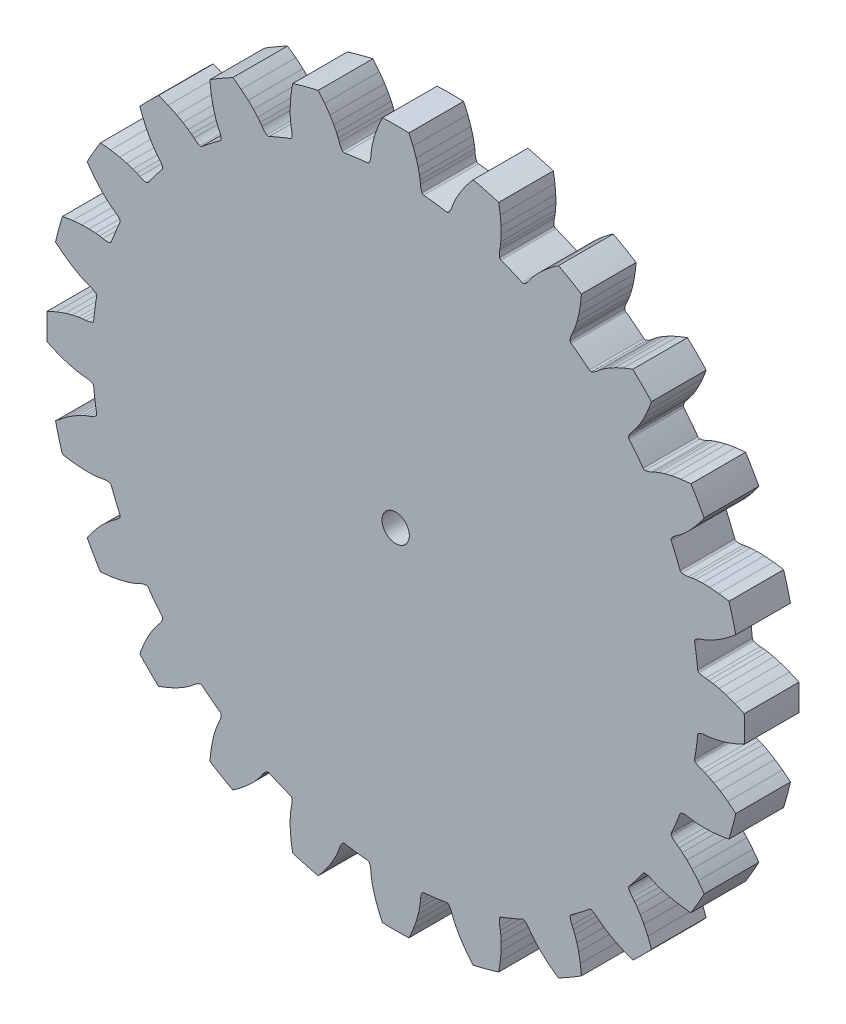
SolidWorks part; units mm, degrees
ref_plane "Front Plane" through (0, 0, 0) normal (0, 0, 1) x (1, 0, 0)
ref_plane "Top Plane" through (0, 0, 0) normal (0, 1, 0) x (1, 0, 0)
ref_plane "Right Plane" through (0, 0, 0) normal (1, 0, 0) x (0, 0, -1)
sketch "Model" plane through (0, 0, 0) normal (0, 0, 1) x (1, 0, 0)
  arc A1 (34.9181, -4.5971) -> (35.0673, -3.2696) centre (0, 0) ccw
  arc A2 (35.2278, -3.0481) -> (35.0673, -3.2696) centre (35.3347, -3.2945) ccw
  arc A3 (35.9833, -2.8721) -> (35.2278, -3.0481) centre (36.0877, -5.0299) ccw
  arc A4 (35.9833, -2.8721) -> (36.3636, -2.8405) centre (35.7172, 2.6237) ccw
  arc A5 (36.3636, -2.8405) -> (36.8336, -2.7716) centre (35.3622, 5.6245) ccw
  arc A6 (36.8336, -2.7716) -> (37.5555, -2.6174) centre (35.1043, 7.0963) ccw
  arc A7 (37.5555, -2.6174) -> (38.3737, -2.3829) centre (34.2966, 10.2971) ccw
  arc A8 (38.3737, -2.3829) -> (39.3866, -2.0164) centre (33.8084, 11.8154) ccw
  arc A9 (39.3866, -2.0164) -> (40.4752, -1.5354) centre (32.5769, 14.869) ccw
  arc A10 (40.4752, -1.5354) -> (40.4752, 1.5354) centre (0, 0) ccw
  arc A11 (40.4752, 1.5354) -> (39.3866, 2.0164) centre (32.5769, -14.869) ccw
  arc A12 (39.3866, 2.0164) -> (38.3737, 2.3829) centre (33.8084, -11.8154) ccw
  arc A13 (38.3737, 2.3829) -> (37.5555, 2.6174) centre (34.2966, -10.2971) ccw
  arc A14 (37.5555, 2.6174) -> (36.8336, 2.7716) centre (35.1043, -7.0963) ccw
  arc A15 (36.8336, 2.7716) -> (36.3636, 2.8405) centre (35.3622, -5.6245) ccw
  arc A16 (36.3636, 2.8405) -> (35.9833, 2.8721) centre (35.7172, -2.6237) ccw
  arc A17 (35.2278, 3.0481) -> (35.9833, 2.8721) centre (36.0877, 5.0299) ccw
  arc A18 (35.0673, 3.2696) -> (35.2278, 3.0481) centre (35.3347, 3.2945) ccw
  arc A19 (35.0673, 3.2696) -> (34.7187, 5.9179) centre (0, 0) ccw
  arc A20 (34.8164, 6.1734) -> (34.7187, 5.9179) centre (34.9834, 5.9631) ccw
  arc A21 (35.5005, 6.5389) -> (34.8164, 6.1734) centre (36.1599, 4.4817) ccw
  arc A22 (35.5005, 6.5389) -> (35.8597, 6.6679) centre (33.8211, 11.7785) ccw
  arc A23 (35.8597, 6.6679) -> (36.2958, 6.8561) centre (32.7015, 14.5853) ccw
  arc A24 (36.2958, 6.8561) -> (36.9533, 7.1918) centre (32.0715, 15.9402) ccw
  arc A25 (36.9533, 7.1918) -> (37.6829, 7.6301) centre (30.4629, 18.8229) ccw
  arc A26 (37.6829, 7.6301) -> (38.5664, 8.2463) centre (29.5984, 20.1631) ccw
  arc A27 (38.5664, 8.2463) -> (39.4934, 8.9927) centre (27.6185, 22.7939) ccw
  arc A28 (39.4934, 8.9927) -> (38.6987, 11.9589) centre (0, 0) ccw
  arc A29 (38.6987, 11.9589) -> (37.5227, 12.1417) centre (35.3153, -5.9309) ccw
  arc A30 (37.5227, 12.1417) -> (36.4494, 12.2336) centre (35.7145, -2.6625) ccw
  arc A31 (36.4494, 12.2336) -> (35.5984, 12.2483) centre (35.7931, -1.0696) ccw
  arc A32 (35.5984, 12.2483) -> (34.8612, 12.2104) centre (35.7448, 2.2311) ccw
  arc A33 (34.8612, 12.2104) -> (34.3894, 12.1553) centre (35.613, 3.7195) ccw
  arc A34 (34.3894, 12.1553) -> (34.0138, 12.0874) centre (35.1792, 6.71) ccw
  arc A35 (33.2386, 12.0619) -> (34.0138, 12.0874) centre (33.5562, 14.1987) ccw
  arc A36 (33.0262, 12.2343) -> (33.2386, 12.0619) centre (33.2781, 12.3275) ccw
  arc A37 (33.0262, 12.2343) -> (32.004, 14.7021) centre (0, 0) ccw
  arc A38 (32.0323, 14.9742) -> (32.004, 14.7021) centre (32.248, 14.8142) ccw
  arc A39 (32.5985, 15.5043) -> (32.0323, 14.9742) centre (33.7678, 13.6878) ccw
  arc A40 (32.5985, 15.5043) -> (32.912, 15.7219) centre (29.6202, 20.1308) ccw
  arc A41 (32.912, 15.7219) -> (33.2846, 16.0165) centre (27.8123, 22.5521) ccw
  arc A42 (33.2846, 16.0165) -> (33.8327, 16.511) centre (26.853, 23.6978) ccw
  arc A43 (33.8327, 16.511) -> (34.4241, 17.1232) centre (24.5532, 26.0659) ccw
  arc A44 (34.4241, 17.1232) -> (35.118, 17.9471) centre (23.3712, 27.1366) ccw
  arc A45 (35.118, 17.9471) -> (35.8203, 18.9079) centre (20.7779, 29.1654) ccw
  arc A46 (35.8203, 18.9079) -> (34.2849, 21.5673) centre (0, 0) ccw
  arc A47 (34.2849, 21.5673) -> (33.1016, 21.4395) centre (35.647, 3.4115) ccw
  arc A48 (33.1016, 21.4395) -> (32.0412, 21.2505) centre (35.1866, 6.6718) ccw
  arc A49 (32.0412, 21.2505) -> (31.2153, 21.0445) centre (34.8503, 8.2307) ccw
  arc A50 (31.2153, 21.0445) -> (30.513, 20.817) centre (33.9494, 11.4065) ccw
  arc A51 (30.513, 20.817) -> (30.0715, 20.6417) centre (33.4369, 12.8101) ccw
  arc A52 (30.0715, 20.6417) -> (29.7263, 20.479) centre (32.2438, 15.5865) ccw
  arc A53 (28.9841, 20.2537) -> (29.7263, 20.479) centre (28.7379, 22.3999) ccw
  arc A54 (28.7344, 20.3652) -> (28.9841, 20.2537) centre (28.9535, 20.5205) ccw
  arc A55 (28.7344, 20.3652) -> (27.1083, 22.4844) centre (0, 0) ccw
  arc A56 (27.0652, 22.7545) -> (27.1083, 22.4844) centre (27.315, 22.6559) ccw
  arc A57 (27.4749, 23.4131) -> (27.0652, 22.7545) centre (29.0746, 21.9612) ccw
  arc A58 (27.4749, 23.4131) -> (27.7215, 23.7044) centre (23.4007, 27.1111) ccw
  arc A59 (27.7215, 23.7044) -> (28.0051, 24.0855) centre (21.0277, 28.982) ccw
  arc A60 (28.0051, 24.0855) -> (28.4066, 24.7049) centre (19.8046, 29.8404) ccw
  arc A61 (28.4066, 24.7049) -> (28.8193, 25.4493) centre (16.9702, 31.5325) ccw
  arc A62 (28.8193, 25.4493) -> (29.2763, 26.4247) centre (15.5514, 32.2609) ccw
  arc A63 (29.2763, 26.4247) -> (29.706, 27.5346) centre (12.5214, 33.5494) ccw
  arc A64 (29.706, 27.5346) -> (27.5346, 29.706) centre (0, 0) ccw
  arc A65 (27.5346, 29.706) -> (26.4247, 29.2763) centre (33.5494, 12.5214) ccw
  arc A66 (26.4247, 29.2763) -> (25.4493, 28.8193) centre (32.2609, 15.5514) ccw
  arc A67 (25.4493, 28.8193) -> (24.7049, 28.4066) centre (31.5325, 16.9702) ccw
  arc A68 (24.7049, 28.4066) -> (24.0855, 28.0051) centre (29.8404, 19.8046) ccw
  arc A69 (24.0855, 28.0051) -> (23.7044, 27.7215) centre (28.982, 21.0277) ccw
  arc A70 (23.7044, 27.7215) -> (23.4131, 27.4749) centre (27.1111, 23.4007) ccw
  arc A71 (22.7545, 27.0652) -> (23.4131, 27.4749) centre (21.9612, 29.0746) ccw
  arc A72 (22.4844, 27.1083) -> (22.7545, 27.0652) centre (22.6559, 27.315) ccw
  arc A73 (22.4844, 27.1083) -> (20.3652, 28.7344) centre (0, 0) ccw
  arc A74 (20.2537, 28.9841) -> (20.3652, 28.7344) centre (20.5205, 28.9535) ccw
  arc A75 (20.479, 29.7263) -> (20.2537, 28.9841) centre (22.3999, 28.7379) ccw
  arc A76 (20.479, 29.7263) -> (20.6417, 30.0715) centre (15.5865, 32.2438) ccw
  arc A77 (20.6417, 30.0715) -> (20.817, 30.513) centre (12.8101, 33.4369) ccw
  arc A78 (20.817, 30.513) -> (21.0445, 31.2153) centre (11.4065, 33.9494) ccw
  arc A79 (21.0445, 31.2153) -> (21.2505, 32.0412) centre (8.2307, 34.8503) ccw
  arc A80 (21.2505, 32.0412) -> (21.4395, 33.1016) centre (6.6718, 35.1866) ccw
  arc A81 (21.4395, 33.1016) -> (21.5673, 34.2849) centre (3.4115, 35.647) ccw
  arc A82 (21.5673, 34.2849) -> (18.9079, 35.8203) centre (0, 0) ccw
  arc A83 (18.9079, 35.8203) -> (17.9471, 35.118) centre (29.1654, 20.7779) ccw
  arc A84 (17.9471, 35.118) -> (17.1232, 34.4241) centre (27.1366, 23.3712) ccw
  arc A85 (17.1232, 34.4241) -> (16.511, 33.8327) centre (26.0659, 24.5532) ccw
  arc A86 (16.511, 33.8327) -> (16.0165, 33.2846) centre (23.6978, 26.853) ccw
  arc A87 (16.0165, 33.2846) -> (15.7219, 32.912) centre (22.5521, 27.8123) ccw
  arc A88 (15.7219, 32.912) -> (15.5043, 32.5985) centre (20.1308, 29.6202) ccw
  arc A89 (14.9742, 32.0323) -> (15.5043, 32.5985) centre (13.6878, 33.7678) ccw
  arc A90 (14.7021, 32.004) -> (14.9742, 32.0323) centre (14.8142, 32.248) ccw
  arc A91 (14.7021, 32.004) -> (12.2343, 33.0262) centre (0, 0) ccw
  arc A92 (12.0619, 33.2386) -> (12.2343, 33.0262) centre (12.3275, 33.2781) ccw
  arc A93 (12.0874, 34.0138) -> (12.0619, 33.2386) centre (14.1987, 33.5562) ccw
  arc A94 (12.0874, 34.0138) -> (12.1553, 34.3894) centre (6.71, 35.1792) ccw
  arc A95 (12.1553, 34.3894) -> (12.2104, 34.8612) centre (3.7195, 35.613) ccw
  arc A96 (12.2104, 34.8612) -> (12.2483, 35.5984) centre (2.2311, 35.7448) ccw
  arc A97 (12.2483, 35.5984) -> (12.2336, 36.4494) centre (-1.0696, 35.7931) ccw
  arc A98 (12.2336, 36.4494) -> (12.1417, 37.5227) centre (-2.6625, 35.7145) ccw
  arc A99 (12.1417, 37.5227) -> (11.9589, 38.6987) centre (-5.9309, 35.3153) ccw
  arc A100 (11.9589, 38.6987) -> (8.9927, 39.4934) centre (0, 0) ccw
  arc A101 (8.9927, 39.4934) -> (8.2463, 38.5664) centre (22.7939, 27.6185) ccw
  arc A102 (8.2463, 38.5664) -> (7.6301, 37.6829) centre (20.1631, 29.5984) ccw
  arc A103 (7.6301, 37.6829) -> (7.1918, 36.9533) centre (18.8229, 30.4629) ccw
  arc A104 (7.1918, 36.9533) -> (6.8561, 36.2958) centre (15.9402, 32.0715) ccw
  arc A105 (6.8561, 36.2958) -> (6.6679, 35.8597) centre (14.5853, 32.7015) ccw
  arc A106 (6.6679, 35.8597) -> (6.5389, 35.5005) centre (11.7785, 33.8211) ccw
  arc A107 (6.1734, 34.8164) -> (6.5389, 35.5005) centre (4.4817, 36.1599) ccw
  arc A108 (5.9179, 34.7187) -> (6.1734, 34.8164) centre (5.9631, 34.9834) ccw
  arc A109 (5.9179, 34.7187) -> (3.2696, 35.0673) centre (0, 0) ccw
  arc A110 (3.0481, 35.2278) -> (3.2696, 35.0673) centre (3.2945, 35.3347) ccw
  arc A111 (2.8721, 35.9833) -> (3.0481, 35.2278) centre (5.0299, 36.0877) ccw
  arc A112 (2.8721, 35.9833) -> (2.8405, 36.3636) centre (-2.6237, 35.7172) ccw
  arc A113 (2.8405, 36.3636) -> (2.7716, 36.8336) centre (-5.6245, 35.3622) ccw
  arc A114 (2.7716, 36.8336) -> (2.6174, 37.5555) centre (-7.0963, 35.1043) ccw
  arc A115 (2.6174, 37.5555) -> (2.3829, 38.3737) centre (-10.2971, 34.2966) ccw
  arc A116 (2.3829, 38.3737) -> (2.0164, 39.3866) centre (-11.8154, 33.8084) ccw
  arc A117 (2.0164, 39.3866) -> (1.5354, 40.4752) centre (-14.869, 32.5769) ccw
  arc A118 (1.5354, 40.4752) -> (-1.5354, 40.4752) centre (0, 0) ccw
  arc A119 (-1.5354, 40.4752) -> (-2.0164, 39.3866) centre (14.869, 32.5769) ccw
  arc A120 (-2.0164, 39.3866) -> (-2.3829, 38.3737) centre (11.8154, 33.8084) ccw
  arc A121 (-2.3829, 38.3737) -> (-2.6174, 37.5555) centre (10.2971, 34.2966) ccw
  arc A122 (-2.6174, 37.5555) -> (-2.7716, 36.8336) centre (7.0963, 35.1043) ccw
  arc A123 (-2.7716, 36.8336) -> (-2.8405, 36.3636) centre (5.6245, 35.3622) ccw
  arc A124 (-2.8405, 36.3636) -> (-2.8721, 35.9833) centre (2.6237, 35.7172) ccw
  arc A125 (-3.0481, 35.2278) -> (-2.8721, 35.9833) centre (-5.0299, 36.0877) ccw
  arc A126 (-3.2696, 35.0673) -> (-3.0481, 35.2278) centre (-3.2945, 35.3347) ccw
  arc A127 (-3.2696, 35.0673) -> (-5.9179, 34.7187) centre (0, 0) ccw
  arc A128 (-6.1734, 34.8164) -> (-5.9179, 34.7187) centre (-5.9631, 34.9834) ccw
  arc A129 (-6.5389, 35.5005) -> (-6.1734, 34.8164) centre (-4.4817, 36.1599) ccw
  arc A130 (-6.5389, 35.5005) -> (-6.6679, 35.8597) centre (-11.7785, 33.8211) ccw
  arc A131 (-6.6679, 35.8597) -> (-6.8561, 36.2958) centre (-14.5853, 32.7015) ccw
  arc A132 (-6.8561, 36.2958) -> (-7.1918, 36.9533) centre (-15.9402, 32.0715) ccw
  arc A133 (-7.1918, 36.9533) -> (-7.6301, 37.6829) centre (-18.8229, 30.4629) ccw
  arc A134 (-7.6301, 37.6829) -> (-8.2463, 38.5664) centre (-20.1631, 29.5984) ccw
  arc A135 (-8.2463, 38.5664) -> (-8.9927, 39.4934) centre (-22.7939, 27.6185) ccw
  arc A136 (-8.9927, 39.4934) -> (-11.9589, 38.6987) centre (0, 0) ccw
  arc A137 (-11.9589, 38.6987) -> (-12.1417, 37.5227) centre (5.9309, 35.3153) ccw
  arc A138 (-12.1417, 37.5227) -> (-12.2336, 36.4494) centre (2.6625, 35.7145) ccw
  arc A139 (-12.2336, 36.4494) -> (-12.2483, 35.5984) centre (1.0696, 35.7931) ccw
  arc A140 (-12.2483, 35.5984) -> (-12.2104, 34.8612) centre (-2.2311, 35.7448) ccw
  arc A141 (-12.2104, 34.8612) -> (-12.1553, 34.3894) centre (-3.7195, 35.613) ccw
  arc A142 (-12.1553, 34.3894) -> (-12.0874, 34.0138) centre (-6.71, 35.1792) ccw
  arc A143 (-12.0619, 33.2386) -> (-12.0874, 34.0138) centre (-14.1987, 33.5562) ccw
  arc A144 (-12.2343, 33.0262) -> (-12.0619, 33.2386) centre (-12.3275, 33.2781) ccw
  arc A145 (-12.2343, 33.0262) -> (-14.7021, 32.004) centre (0, 0) ccw
  arc A146 (-14.9742, 32.0323) -> (-14.7021, 32.004) centre (-14.8142, 32.248) ccw
  arc A147 (-15.5043, 32.5985) -> (-14.9742, 32.0323) centre (-13.6878, 33.7678) ccw
  arc A148 (-15.5043, 32.5985) -> (-15.7219, 32.912) centre (-20.1308, 29.6202) ccw
  arc A149 (-15.7219, 32.912) -> (-16.0165, 33.2846) centre (-22.5521, 27.8123) ccw
  arc A150 (-16.0165, 33.2846) -> (-16.511, 33.8327) centre (-23.6978, 26.853) ccw
  arc A151 (-16.511, 33.8327) -> (-17.1232, 34.4241) centre (-26.0659, 24.5532) ccw
  arc A152 (-17.1232, 34.4241) -> (-17.9471, 35.118) centre (-27.1366, 23.3712) ccw
  arc A153 (-17.9471, 35.118) -> (-18.9079, 35.8203) centre (-29.1654, 20.7779) ccw
  arc A154 (-18.9079, 35.8203) -> (-21.5673, 34.2849) centre (0, 0) ccw
  arc A155 (-21.5673, 34.2849) -> (-21.4395, 33.1016) centre (-3.4115, 35.647) ccw
  arc A156 (-21.4395, 33.1016) -> (-21.2505, 32.0412) centre (-6.6718, 35.1866) ccw
  arc A157 (-21.2505, 32.0412) -> (-21.0445, 31.2153) centre (-8.2307, 34.8503) ccw
  arc A158 (-21.0445, 31.2153) -> (-20.817, 30.513) centre (-11.4065, 33.9494) ccw
  arc A159 (-20.817, 30.513) -> (-20.6417, 30.0715) centre (-12.8101, 33.4369) ccw
  arc A160 (-20.6417, 30.0715) -> (-20.479, 29.7263) centre (-15.5865, 32.2438) ccw
  arc A161 (-20.2537, 28.9841) -> (-20.479, 29.7263) centre (-22.3999, 28.7379) ccw
  arc A162 (-20.3652, 28.7344) -> (-20.2537, 28.9841) centre (-20.5205, 28.9535) ccw
  arc A163 (-20.3652, 28.7344) -> (-22.4844, 27.1083) centre (0, 0) ccw
  arc A164 (-22.7545, 27.0652) -> (-22.4844, 27.1083) centre (-22.6559, 27.315) ccw
  arc A165 (-23.4131, 27.4749) -> (-22.7545, 27.0652) centre (-21.9612, 29.0746) ccw
  arc A166 (-23.4131, 27.4749) -> (-23.7044, 27.7215) centre (-27.1111, 23.4007) ccw
  arc A167 (-23.7044, 27.7215) -> (-24.0855, 28.0051) centre (-28.982, 21.0277) ccw
  arc A168 (-24.0855, 28.0051) -> (-24.7049, 28.4066) centre (-29.8404, 19.8046) ccw
  arc A169 (-24.7049, 28.4066) -> (-25.4493, 28.8193) centre (-31.5325, 16.9702) ccw
  arc A170 (-25.4493, 28.8193) -> (-26.4247, 29.2763) centre (-32.2609, 15.5514) ccw
  arc A171 (-26.4247, 29.2763) -> (-27.5346, 29.706) centre (-33.5494, 12.5214) ccw
  arc A172 (-27.5346, 29.706) -> (-29.706, 27.5346) centre (0, 0) ccw
  arc A173 (-29.706, 27.5346) -> (-29.2763, 26.4247) centre (-12.5214, 33.5494) ccw
  arc A174 (-29.2763, 26.4247) -> (-28.8193, 25.4493) centre (-15.5514, 32.2609) ccw
  arc A175 (-28.8193, 25.4493) -> (-28.4066, 24.7049) centre (-16.9702, 31.5325) ccw
  arc A176 (-28.4066, 24.7049) -> (-28.0051, 24.0855) centre (-19.8046, 29.8404) ccw
  arc A177 (-28.0051, 24.0855) -> (-27.7215, 23.7044) centre (-21.0277, 28.982) ccw
  arc A178 (-27.7215, 23.7044) -> (-27.4749, 23.4131) centre (-23.4007, 27.1111) ccw
  arc A179 (-27.0652, 22.7545) -> (-27.4749, 23.4131) centre (-29.0746, 21.9612) ccw
  arc A180 (-27.1083, 22.4844) -> (-27.0652, 22.7545) centre (-27.315, 22.6559) ccw
  arc A181 (-27.1083, 22.4844) -> (-28.7344, 20.3652) centre (0, 0) ccw
  arc A182 (-28.9841, 20.2537) -> (-28.7344, 20.3652) centre (-28.9535, 20.5205) ccw
  arc A183 (-29.7263, 20.479) -> (-28.9841, 20.2537) centre (-28.7379, 22.3999) ccw
  arc A184 (-29.7263, 20.479) -> (-30.0715, 20.6417) centre (-32.2438, 15.5865) ccw
  arc A185 (-30.0715, 20.6417) -> (-30.513, 20.817) centre (-33.4369, 12.8101) ccw
  arc A186 (-30.513, 20.817) -> (-31.2153, 21.0445) centre (-33.9494, 11.4065) ccw
  arc A187 (-31.2153, 21.0445) -> (-32.0412, 21.2505) centre (-34.8503, 8.2307) ccw
  arc A188 (-32.0412, 21.2505) -> (-33.1016, 21.4395) centre (-35.1866, 6.6718) ccw
  arc A189 (-33.1016, 21.4395) -> (-34.2849, 21.5673) centre (-35.647, 3.4115) ccw
  arc A190 (-34.2849, 21.5673) -> (-35.8203, 18.9079) centre (0, 0) ccw
  arc A191 (-35.8203, 18.9079) -> (-35.118, 17.9471) centre (-20.7779, 29.1654) ccw
  arc A192 (-35.118, 17.9471) -> (-34.4241, 17.1232) centre (-23.3712, 27.1366) ccw
  arc A193 (-34.4241, 17.1232) -> (-33.8327, 16.511) centre (-24.5532, 26.0659) ccw
  arc A194 (-33.8327, 16.511) -> (-33.2846, 16.0165) centre (-26.853, 23.6978) ccw
  arc A195 (-33.2846, 16.0165) -> (-32.912, 15.7219) centre (-27.8123, 22.5521) ccw
  arc A196 (-32.912, 15.7219) -> (-32.5985, 15.5043) centre (-29.6202, 20.1308) ccw
  arc A197 (-32.0323, 14.9742) -> (-32.5985, 15.5043) centre (-33.7678, 13.6878) ccw
  arc A198 (-32.004, 14.7021) -> (-32.0323, 14.9742) centre (-32.248, 14.8142) ccw
  arc A199 (-32.004, 14.7021) -> (-33.0262, 12.2343) centre (0, 0) ccw
  arc A200 (-33.2386, 12.0619) -> (-33.0262, 12.2343) centre (-33.2781, 12.3275) ccw
  arc A201 (-34.0138, 12.0874) -> (-33.2386, 12.0619) centre (-33.5562, 14.1987) ccw
  arc A202 (-34.0138, 12.0874) -> (-34.3894, 12.1553) centre (-35.1792, 6.71) ccw
  arc A203 (-34.3894, 12.1553) -> (-34.8612, 12.2104) centre (-35.613, 3.7195) ccw
  arc A204 (-34.8612, 12.2104) -> (-35.5984, 12.2483) centre (-35.7448, 2.2311) ccw
  arc A205 (-35.5984, 12.2483) -> (-36.4494, 12.2336) centre (-35.7931, -1.0696) ccw
  arc A206 (-36.4494, 12.2336) -> (-37.5227, 12.1417) centre (-35.7145, -2.6625) ccw
  arc A207 (-37.5227, 12.1417) -> (-38.6987, 11.9589) centre (-35.3153, -5.9309) ccw
  arc A208 (-38.6987, 11.9589) -> (-39.4934, 8.9927) centre (0, 0) ccw
  arc A209 (-39.4934, 8.9927) -> (-38.5664, 8.2463) centre (-27.6185, 22.7939) ccw
  arc A210 (-38.5664, 8.2463) -> (-37.6829, 7.6301) centre (-29.5984, 20.1631) ccw
  arc A211 (-37.6829, 7.6301) -> (-36.9533, 7.1918) centre (-30.4629, 18.8229) ccw
  arc A212 (-36.9533, 7.1918) -> (-36.2958, 6.8561) centre (-32.0715, 15.9402) ccw
  arc A213 (-36.2958, 6.8561) -> (-35.8597, 6.6679) centre (-32.7015, 14.5853) ccw
  arc A214 (-35.8597, 6.6679) -> (-35.5005, 6.5389) centre (-33.8211, 11.7785) ccw
  arc A215 (-34.8164, 6.1734) -> (-35.5005, 6.5389) centre (-36.1599, 4.4817) ccw
  arc A216 (-34.7187, 5.9179) -> (-34.8164, 6.1734) centre (-34.9834, 5.9631) ccw
  arc A217 (-34.7187, 5.9179) -> (-35.0673, 3.2696) centre (0, 0) ccw
  arc A218 (-35.2278, 3.0481) -> (-35.0673, 3.2696) centre (-35.3347, 3.2945) ccw
  arc A219 (-35.9833, 2.8721) -> (-35.2278, 3.0481) centre (-36.0877, 5.0299) ccw
  arc A220 (-35.9833, 2.8721) -> (-36.3636, 2.8405) centre (-35.7172, -2.6237) ccw
  arc A221 (-36.3636, 2.8405) -> (-36.8336, 2.7716) centre (-35.3622, -5.6245) ccw
  arc A222 (-36.8336, 2.7716) -> (-37.5555, 2.6174) centre (-35.1043, -7.0963) ccw
  arc A223 (-37.5555, 2.6174) -> (-38.3737, 2.3829) centre (-34.2966, -10.2971) ccw
  arc A224 (-38.3737, 2.3829) -> (-39.3866, 2.0164) centre (-33.8084, -11.8154) ccw
  arc A225 (-39.3866, 2.0164) -> (-40.4752, 1.5354) centre (-32.5769, -14.869) ccw
  arc A226 (-40.4752, 1.5354) -> (-40.4752, -1.5354) centre (0, 0) ccw
  arc A227 (-40.4752, -1.5354) -> (-39.3866, -2.0164) centre (-32.5769, 14.869) ccw
  arc A228 (-39.3866, -2.0164) -> (-38.3737, -2.3829) centre (-33.8084, 11.8154) ccw
  arc A229 (-38.3737, -2.3829) -> (-37.5555, -2.6174) centre (-34.2966, 10.2971) ccw
  arc A230 (-37.5555, -2.6174) -> (-36.8336, -2.7716) centre (-35.1043, 7.0963) ccw
  arc A231 (-36.8336, -2.7716) -> (-36.3636, -2.8405) centre (-35.3622, 5.6245) ccw
  arc A232 (-36.3636, -2.8405) -> (-35.9833, -2.8721) centre (-35.7172, 2.6237) ccw
  arc A233 (-35.2278, -3.0481) -> (-35.9833, -2.8721) centre (-36.0877, -5.0299) ccw
  arc A234 (-35.0673, -3.2696) -> (-35.2278, -3.0481) centre (-35.3347, -3.2945) ccw
  arc A235 (-35.0673, -3.2696) -> (-34.7187, -5.9179) centre (0, 0) ccw
  arc A236 (-34.8164, -6.1734) -> (-34.7187, -5.9179) centre (-34.9834, -5.9631) ccw
  arc A237 (-35.5005, -6.5389) -> (-34.8164, -6.1734) centre (-36.1599, -4.4817) ccw
  arc A238 (-35.5005, -6.5389) -> (-35.8597, -6.6679) centre (-33.8211, -11.7785) ccw
  arc A239 (-35.8597, -6.6679) -> (-36.2958, -6.8561) centre (-32.7015, -14.5853) ccw
  arc A240 (-36.2958, -6.8561) -> (-36.9533, -7.1918) centre (-32.0715, -15.9402) ccw
  arc A241 (-36.9533, -7.1918) -> (-37.6829, -7.6301) centre (-30.4629, -18.8229) ccw
  arc A242 (-37.6829, -7.6301) -> (-38.5664, -8.2463) centre (-29.5984, -20.1631) ccw
  arc A243 (-38.5664, -8.2463) -> (-39.4934, -8.9927) centre (-27.6185, -22.7939) ccw
  arc A244 (-39.4934, -8.9927) -> (-38.6987, -11.9589) centre (0, 0) ccw
  arc A245 (-38.6987, -11.9589) -> (-37.5227, -12.1417) centre (-35.3153, 5.9309) ccw
  arc A246 (-37.5227, -12.1417) -> (-36.4494, -12.2336) centre (-35.7145, 2.6625) ccw
  arc A247 (-36.4494, -12.2336) -> (-35.5984, -12.2483) centre (-35.7931, 1.0696) ccw
  arc A248 (-35.5984, -12.2483) -> (-34.8612, -12.2104) centre (-35.7448, -2.2311) ccw
  arc A249 (-34.8612, -12.2104) -> (-34.3894, -12.1553) centre (-35.613, -3.7195) ccw
  arc A250 (-34.3894, -12.1553) -> (-34.0138, -12.0874) centre (-35.1792, -6.71) ccw
  arc A251 (-33.2386, -12.0619) -> (-34.0138, -12.0874) centre (-33.5562, -14.1987) ccw
  arc A252 (-33.0262, -12.2343) -> (-33.2386, -12.0619) centre (-33.2781, -12.3275) ccw
  arc A253 (-33.0262, -12.2343) -> (-32.004, -14.7021) centre (0, 0) ccw
  arc A254 (-32.0323, -14.9742) -> (-32.004, -14.7021) centre (-32.248, -14.8142) ccw
  arc A255 (-32.5985, -15.5043) -> (-32.0323, -14.9742) centre (-33.7678, -13.6878) ccw
  arc A256 (-32.5985, -15.5043) -> (-32.912, -15.7219) centre (-29.6202, -20.1308) ccw
  arc A257 (-32.912, -15.7219) -> (-33.2846, -16.0165) centre (-27.8123, -22.5521) ccw
  arc A258 (-33.2846, -16.0165) -> (-33.8327, -16.511) centre (-26.853, -23.6978) ccw
  arc A259 (-33.8327, -16.511) -> (-34.4241, -17.1232) centre (-24.5532, -26.0659) ccw
  arc A260 (-34.4241, -17.1232) -> (-35.118, -17.9471) centre (-23.3712, -27.1366) ccw
  arc A261 (-35.118, -17.9471) -> (-35.8203, -18.9079) centre (-20.7779, -29.1654) ccw
  arc A262 (-35.8203, -18.9079) -> (-34.2849, -21.5673) centre (0, 0) ccw
  arc A263 (-34.2849, -21.5673) -> (-33.1016, -21.4395) centre (-35.647, -3.4115) ccw
  arc A264 (-33.1016, -21.4395) -> (-32.0412, -21.2505) centre (-35.1866, -6.6718) ccw
  arc A265 (-32.0412, -21.2505) -> (-31.2153, -21.0445) centre (-34.8503, -8.2307) ccw
  arc A266 (-31.2153, -21.0445) -> (-30.513, -20.817) centre (-33.9494, -11.4065) ccw
  arc A267 (-30.513, -20.817) -> (-30.0715, -20.6417) centre (-33.4369, -12.8101) ccw
  arc A268 (-30.0715, -20.6417) -> (-29.7263, -20.479) centre (-32.2438, -15.5865) ccw
  arc A269 (-28.9841, -20.2537) -> (-29.7263, -20.479) centre (-28.7379, -22.3999) ccw
  arc A270 (-28.7344, -20.3652) -> (-28.9841, -20.2537) centre (-28.9535, -20.5205) ccw
  arc A271 (-28.7344, -20.3652) -> (-27.1083, -22.4844) centre (0, 0) ccw
  arc A272 (-27.0652, -22.7545) -> (-27.1083, -22.4844) centre (-27.315, -22.6559) ccw
  arc A273 (-27.4749, -23.4131) -> (-27.0652, -22.7545) centre (-29.0746, -21.9612) ccw
  arc A274 (-27.4749, -23.4131) -> (-27.7215, -23.7044) centre (-23.4007, -27.1111) ccw
  arc A275 (-27.7215, -23.7044) -> (-28.0051, -24.0855) centre (-21.0277, -28.982) ccw
  arc A276 (-28.0051, -24.0855) -> (-28.4066, -24.7049) centre (-19.8046, -29.8404) ccw
  arc A277 (-28.4066, -24.7049) -> (-28.8193, -25.4493) centre (-16.9702, -31.5325) ccw
  arc A278 (-28.8193, -25.4493) -> (-29.2763, -26.4247) centre (-15.5514, -32.2609) ccw
  arc A279 (-29.2763, -26.4247) -> (-29.706, -27.5346) centre (-12.5214, -33.5494) ccw
  arc A280 (-29.706, -27.5346) -> (-27.5346, -29.706) centre (0, 0) ccw
  arc A281 (-27.5346, -29.706) -> (-26.4247, -29.2763) centre (-33.5494, -12.5214) ccw
  arc A282 (-26.4247, -29.2763) -> (-25.4493, -28.8193) centre (-32.2609, -15.5514) ccw
  arc A283 (-25.4493, -28.8193) -> (-24.7049, -28.4066) centre (-31.5325, -16.9702) ccw
  arc A284 (-24.7049, -28.4066) -> (-24.0855, -28.0051) centre (-29.8404, -19.8046) ccw
  arc A285 (-24.0855, -28.0051) -> (-23.7044, -27.7215) centre (-28.982, -21.0277) ccw
  arc A286 (-23.7044, -27.7215) -> (-23.4131, -27.4749) centre (-27.1111, -23.4007) ccw
  arc A287 (-22.7545, -27.0652) -> (-23.4131, -27.4749) centre (-21.9612, -29.0746) ccw
  arc A288 (-22.4844, -27.1083) -> (-22.7545, -27.0652) centre (-22.6559, -27.315) ccw
  arc A289 (-22.4844, -27.1083) -> (-20.3652, -28.7344) centre (0, 0) ccw
  arc A290 (-20.2537, -28.9841) -> (-20.3652, -28.7344) centre (-20.5205, -28.9535) ccw
  arc A291 (-20.479, -29.7263) -> (-20.2537, -28.9841) centre (-22.3999, -28.7379) ccw
  arc A292 (-20.479, -29.7263) -> (-20.6417, -30.0715) centre (-15.5865, -32.2438) ccw
  arc A293 (-20.6417, -30.0715) -> (-20.817, -30.513) centre (-12.8101, -33.4369) ccw
  arc A294 (-20.817, -30.513) -> (-21.0445, -31.2153) centre (-11.4065, -33.9494) ccw
  arc A295 (-21.0445, -31.2153) -> (-21.2505, -32.0412) centre (-8.2307, -34.8503) ccw
  arc A296 (-21.2505, -32.0412) -> (-21.4395, -33.1016) centre (-6.6718, -35.1866) ccw
  arc A297 (-21.4395, -33.1016) -> (-21.5673, -34.2849) centre (-3.4115, -35.647) ccw
  arc A298 (-21.5673, -34.2849) -> (-18.9079, -35.8203) centre (0, 0) ccw
  arc A299 (-18.9079, -35.8203) -> (-17.9471, -35.118) centre (-29.1654, -20.7779) ccw
  arc A300 (-17.9471, -35.118) -> (-17.1232, -34.4241) centre (-27.1366, -23.3712) ccw
  arc A301 (-17.1232, -34.4241) -> (-16.511, -33.8327) centre (-26.0659, -24.5532) ccw
  arc A302 (-16.511, -33.8327) -> (-16.0165, -33.2846) centre (-23.6978, -26.853) ccw
  arc A303 (-16.0165, -33.2846) -> (-15.7219, -32.912) centre (-22.5521, -27.8123) ccw
  arc A304 (-15.7219, -32.912) -> (-15.5043, -32.5985) centre (-20.1308, -29.6202) ccw
  arc A305 (-14.9742, -32.0323) -> (-15.5043, -32.5985) centre (-13.6878, -33.7678) ccw
  arc A306 (-14.7021, -32.004) -> (-14.9742, -32.0323) centre (-14.8142, -32.248) ccw
  arc A307 (-14.7021, -32.004) -> (-12.2343, -33.0262) centre (0, 0) ccw
  arc A308 (-12.0619, -33.2386) -> (-12.2343, -33.0262) centre (-12.3275, -33.2781) ccw
  arc A309 (-12.0874, -34.0138) -> (-12.0619, -33.2386) centre (-14.1987, -33.5562) ccw
  arc A310 (-12.0874, -34.0138) -> (-12.1553, -34.3894) centre (-6.71, -35.1792) ccw
  arc A311 (-12.1553, -34.3894) -> (-12.2104, -34.8612) centre (-3.7195, -35.613) ccw
  arc A312 (-12.2104, -34.8612) -> (-12.2483, -35.5984) centre (-2.2311, -35.7448) ccw
  arc A313 (-12.2483, -35.5984) -> (-12.2336, -36.4494) centre (1.0696, -35.7931) ccw
  arc A314 (-12.2336, -36.4494) -> (-12.1417, -37.5227) centre (2.6625, -35.7145) ccw
  arc A315 (-12.1417, -37.5227) -> (-11.9589, -38.6987) centre (5.9309, -35.3153) ccw
  arc A316 (-11.9589, -38.6987) -> (-8.9927, -39.4934) centre (0, 0) ccw
  arc A317 (-8.9927, -39.4934) -> (-8.2463, -38.5664) centre (-22.7939, -27.6185) ccw
  arc A318 (-8.2463, -38.5664) -> (-7.6301, -37.6829) centre (-20.1631, -29.5984) ccw
  arc A319 (-7.6301, -37.6829) -> (-7.1918, -36.9533) centre (-18.8229, -30.4629) ccw
  arc A320 (-7.1918, -36.9533) -> (-6.8561, -36.2958) centre (-15.9402, -32.0715) ccw
  arc A321 (-6.8561, -36.2958) -> (-6.6679, -35.8597) centre (-14.5853, -32.7015) ccw
  arc A322 (-6.6679, -35.8597) -> (-6.5389, -35.5005) centre (-11.7785, -33.8211) ccw
  arc A323 (-6.1734, -34.8164) -> (-6.5389, -35.5005) centre (-4.4817, -36.1599) ccw
  arc A324 (-5.9179, -34.7187) -> (-6.1734, -34.8164) centre (-5.9631, -34.9834) ccw
  arc A325 (-5.9179, -34.7187) -> (-3.2696, -35.0673) centre (0, 0) ccw
  arc A326 (-3.0481, -35.2278) -> (-3.2696, -35.0673) centre (-3.2945, -35.3347) ccw
  arc A327 (-2.8721, -35.9833) -> (-3.0481, -35.2278) centre (-5.0299, -36.0877) ccw
  arc A328 (-2.8721, -35.9833) -> (-2.8405, -36.3636) centre (2.6237, -35.7172) ccw
  arc A329 (-2.8405, -36.3636) -> (-2.7716, -36.8336) centre (5.6245, -35.3622) ccw
  arc A330 (-2.7716, -36.8336) -> (-2.6174, -37.5555) centre (7.0963, -35.1043) ccw
  arc A331 (-2.6174, -37.5555) -> (-2.3829, -38.3737) centre (10.2971, -34.2966) ccw
  arc A332 (-2.3829, -38.3737) -> (-2.0164, -39.3866) centre (11.8154, -33.8084) ccw
  arc A333 (-2.0164, -39.3866) -> (-1.5354, -40.4752) centre (14.869, -32.5769) ccw
  arc A334 (-1.5354, -40.4752) -> (1.5354, -40.4752) centre (0, 0) ccw
  arc A335 (1.5354, -40.4752) -> (2.0164, -39.3866) centre (-14.869, -32.5769) ccw
  arc A336 (2.0164, -39.3866) -> (2.3829, -38.3737) centre (-11.8154, -33.8084) ccw
  arc A337 (2.3829, -38.3737) -> (2.6174, -37.5555) centre (-10.2971, -34.2966) ccw
  arc A338 (2.6174, -37.5555) -> (2.7716, -36.8336) centre (-7.0963, -35.1043) ccw
  arc A339 (2.7716, -36.8336) -> (2.8405, -36.3636) centre (-5.6245, -35.3622) ccw
  arc A340 (2.8405, -36.3636) -> (2.8721, -35.9833) centre (-2.6237, -35.7172) ccw
  arc A341 (3.0481, -35.2278) -> (2.8721, -35.9833) centre (5.0299, -36.0877) ccw
  arc A342 (3.2696, -35.0673) -> (3.0481, -35.2278) centre (3.2945, -35.3347) ccw
  arc A343 (3.2696, -35.0673) -> (5.9179, -34.7187) centre (0, 0) ccw
  arc A344 (6.1734, -34.8164) -> (5.9179, -34.7187) centre (5.9631, -34.9834) ccw
  arc A345 (6.5389, -35.5005) -> (6.1734, -34.8164) centre (4.4817, -36.1599) ccw
  arc A346 (6.5389, -35.5005) -> (6.6679, -35.8597) centre (11.7785, -33.8211) ccw
  arc A347 (6.6679, -35.8597) -> (6.8561, -36.2958) centre (14.5853, -32.7015) ccw
  arc A348 (6.8561, -36.2958) -> (7.1918, -36.9533) centre (15.9402, -32.0715) ccw
  arc A349 (7.1918, -36.9533) -> (7.6301, -37.6829) centre (18.8229, -30.4629) ccw
  arc A350 (7.6301, -37.6829) -> (8.2463, -38.5664) centre (20.1631, -29.5984) ccw
  arc A351 (8.2463, -38.5664) -> (8.9927, -39.4934) centre (22.7939, -27.6185) ccw
  arc A352 (8.9927, -39.4934) -> (11.9589, -38.6987) centre (0, 0) ccw
  arc A353 (11.9589, -38.6987) -> (12.1417, -37.5227) centre (-5.9309, -35.3153) ccw
  arc A354 (12.1417, -37.5227) -> (12.2336, -36.4494) centre (-2.6625, -35.7145) ccw
  arc A355 (12.2336, -36.4494) -> (12.2483, -35.5984) centre (-1.0696, -35.7931) ccw
  arc A356 (12.2483, -35.5984) -> (12.2104, -34.8612) centre (2.2311, -35.7448) ccw
  arc A357 (12.2104, -34.8612) -> (12.1553, -34.3894) centre (3.7195, -35.613) ccw
  arc A358 (12.1553, -34.3894) -> (12.0874, -34.0138) centre (6.71, -35.1792) ccw
  arc A359 (12.0619, -33.2386) -> (12.0874, -34.0138) centre (14.1987, -33.5562) ccw
  arc A360 (12.2343, -33.0262) -> (12.0619, -33.2386) centre (12.3275, -33.2781) ccw
  arc A361 (12.2343, -33.0262) -> (14.7021, -32.004) centre (0, 0) ccw
  arc A362 (14.9742, -32.0323) -> (14.7021, -32.004) centre (14.8142, -32.248) ccw
  arc A363 (15.5043, -32.5985) -> (14.9742, -32.0323) centre (13.6878, -33.7678) ccw
  arc A364 (15.5043, -32.5985) -> (15.7219, -32.912) centre (20.1308, -29.6202) ccw
  arc A365 (15.7219, -32.912) -> (16.0165, -33.2846) centre (22.5521, -27.8123) ccw
  arc A366 (16.0165, -33.2846) -> (16.511, -33.8327) centre (23.6978, -26.853) ccw
  arc A367 (16.511, -33.8327) -> (17.1232, -34.4241) centre (26.0659, -24.5532) ccw
  arc A368 (17.1232, -34.4241) -> (17.9471, -35.118) centre (27.1366, -23.3712) ccw
  arc A369 (17.9471, -35.118) -> (18.9079, -35.8203) centre (29.1654, -20.7779) ccw
  arc A370 (18.9079, -35.8203) -> (21.5673, -34.2849) centre (0, 0) ccw
  arc A371 (21.5673, -34.2849) -> (21.4395, -33.1016) centre (3.4115, -35.647) ccw
  arc A372 (21.4395, -33.1016) -> (21.2505, -32.0412) centre (6.6718, -35.1866) ccw
  arc A373 (21.2505, -32.0412) -> (21.0445, -31.2153) centre (8.2307, -34.8503) ccw
  arc A374 (21.0445, -31.2153) -> (20.817, -30.513) centre (11.4065, -33.9494) ccw
  arc A375 (20.817, -30.513) -> (20.6417, -30.0715) centre (12.8101, -33.4369) ccw
  arc A376 (20.6417, -30.0715) -> (20.479, -29.7263) centre (15.5865, -32.2438) ccw
  arc A377 (20.2537, -28.9841) -> (20.479, -29.7263) centre (22.3999, -28.7379) ccw
  arc A378 (20.3652, -28.7344) -> (20.2537, -28.9841) centre (20.5205, -28.9535) ccw
  arc A379 (20.3652, -28.7344) -> (22.4844, -27.1083) centre (0, 0) ccw
  arc A380 (22.7545, -27.0652) -> (22.4844, -27.1083) centre (22.6559, -27.315) ccw
  arc A381 (23.4131, -27.4749) -> (22.7545, -27.0652) centre (21.9612, -29.0746) ccw
  arc A382 (23.4131, -27.4749) -> (23.7044, -27.7215) centre (27.1111, -23.4007) ccw
  arc A383 (23.7044, -27.7215) -> (24.0855, -28.0051) centre (28.982, -21.0277) ccw
  arc A384 (24.0855, -28.0051) -> (24.7049, -28.4066) centre (29.8404, -19.8046) ccw
  arc A385 (24.7049, -28.4066) -> (25.4493, -28.8193) centre (31.5325, -16.9702) ccw
  arc A386 (25.4493, -28.8193) -> (26.4247, -29.2763) centre (32.2609, -15.5514) ccw
  arc A387 (26.4247, -29.2763) -> (27.5346, -29.706) centre (33.5494, -12.5214) ccw
  arc A388 (27.5346, -29.706) -> (29.706, -27.5346) centre (0, 0) ccw
  arc A389 (29.706, -27.5346) -> (29.2763, -26.4247) centre (12.5214, -33.5494) ccw
  arc A390 (29.2763, -26.4247) -> (28.8193, -25.4493) centre (15.5514, -32.2609) ccw
  arc A391 (28.8193, -25.4493) -> (28.4066, -24.7049) centre (16.9702, -31.5325) ccw
  arc A392 (28.4066, -24.7049) -> (28.0051, -24.0855) centre (19.8046, -29.8404) ccw
  arc A393 (28.0051, -24.0855) -> (27.7215, -23.7044) centre (21.0277, -28.982) ccw
  arc A394 (27.7215, -23.7044) -> (27.4749, -23.4131) centre (23.4007, -27.1111) ccw
  arc A395 (27.0652, -22.7545) -> (27.4749, -23.4131) centre (29.0746, -21.9612) ccw
  arc A396 (27.1083, -22.4844) -> (27.0652, -22.7545) centre (27.315, -22.6559) ccw
  arc A397 (27.1083, -22.4844) -> (28.7344, -20.3652) centre (0, 0) ccw
  arc A398 (28.9841, -20.2537) -> (28.7344, -20.3652) centre (28.9535, -20.5205) ccw
  arc A399 (29.7263, -20.479) -> (28.9841, -20.2537) centre (28.7379, -22.3999) ccw
  arc A400 (29.7263, -20.479) -> (30.0715, -20.6417) centre (32.2438, -15.5865) ccw
  arc A401 (30.0715, -20.6417) -> (30.513, -20.817) centre (33.4369, -12.8101) ccw
  arc A402 (30.513, -20.817) -> (31.2153, -21.0445) centre (33.9494, -11.4065) ccw
  arc A403 (31.2153, -21.0445) -> (32.0412, -21.2505) centre (34.8503, -8.2307) ccw
  arc A404 (32.0412, -21.2505) -> (33.1016, -21.4395) centre (35.1866, -6.6718) ccw
  arc A405 (33.1016, -21.4395) -> (34.2849, -21.5673) centre (35.647, -3.4115) ccw
  arc A406 (34.2849, -21.5673) -> (35.8203, -18.9079) centre (0, 0) ccw
  arc A407 (35.8203, -18.9079) -> (35.118, -17.9471) centre (20.7779, -29.1654) ccw
  arc A408 (35.118, -17.9471) -> (34.4241, -17.1232) centre (23.3712, -27.1366) ccw
  arc A409 (34.4241, -17.1232) -> (33.8327, -16.511) centre (24.5532, -26.0659) ccw
  arc A410 (33.8327, -16.511) -> (33.2846, -16.0165) centre (26.853, -23.6978) ccw
  arc A411 (33.2846, -16.0165) -> (32.912, -15.7219) centre (27.8123, -22.5521) ccw
  arc A412 (32.912, -15.7219) -> (32.5985, -15.5043) centre (29.6202, -20.1308) ccw
  arc A413 (32.0323, -14.9742) -> (32.5985, -15.5043) centre (33.7678, -13.6878) ccw
  arc A414 (32.004, -14.7021) -> (32.0323, -14.9742) centre (32.248, -14.8142) ccw
  arc A415 (32.004, -14.7021) -> (33.0262, -12.2343) centre (0, 0) ccw
  arc A416 (33.2386, -12.0619) -> (33.0262, -12.2343) centre (33.2781, -12.3275) ccw
  arc A417 (34.0138, -12.0874) -> (33.2386, -12.0619) centre (33.5562, -14.1987) ccw
  arc A418 (34.0138, -12.0874) -> (34.3894, -12.1553) centre (35.1792, -6.71) ccw
  arc A419 (34.3894, -12.1553) -> (34.8612, -12.2104) centre (35.613, -3.7195) ccw
  arc A420 (34.8612, -12.2104) -> (35.5984, -12.2483) centre (35.7448, -2.2311) ccw
  arc A421 (35.5984, -12.2483) -> (36.4494, -12.2336) centre (35.7931, 1.0696) ccw
  arc A422 (36.4494, -12.2336) -> (37.5227, -12.1417) centre (35.7145, 2.6625) ccw
  arc A423 (37.5227, -12.1417) -> (38.6987, -11.9589) centre (35.3153, 5.9309) ccw
  arc A424 (38.6987, -11.9589) -> (39.4934, -8.9927) centre (0, 0) ccw
  arc A425 (39.4934, -8.9927) -> (38.5664, -8.2463) centre (27.6185, -22.7939) ccw
  arc A426 (38.5664, -8.2463) -> (37.6829, -7.6301) centre (29.5984, -20.1631) ccw
  arc A427 (37.6829, -7.6301) -> (36.9533, -7.1918) centre (30.4629, -18.8229) ccw
  arc A428 (36.9533, -7.1918) -> (36.2958, -6.8561) centre (32.0715, -15.9402) ccw
  arc A429 (36.2958, -6.8561) -> (35.8597, -6.6679) centre (32.7015, -14.5853) ccw
  arc A430 (35.8597, -6.6679) -> (35.5005, -6.5389) centre (33.8211, -11.7785) ccw
  arc A431 (34.8164, -6.1734) -> (35.5005, -6.5389) centre (36.1599, -4.4817) ccw
  arc A432 (34.7187, -5.9179) -> (34.8164, -6.1734) centre (34.9834, -5.9631) ccw
  arc A433 (34.7187, -5.9179) -> (34.9181, -4.5971) centre (0, 0) ccw
extrude "Boss-Extrude1" add sketch "Model" along normal blind 6.35
sketch "Sketch2" plane through (0, 0, 6.35) normal (0, 0, 1) x (1, 0, 0)
  circle A0 centre (0, 0) radius 1.5875
  dimension "D1" = 3.175
extrude "Cut-Extrude1" cut sketch "Sketch2" against normal through all
